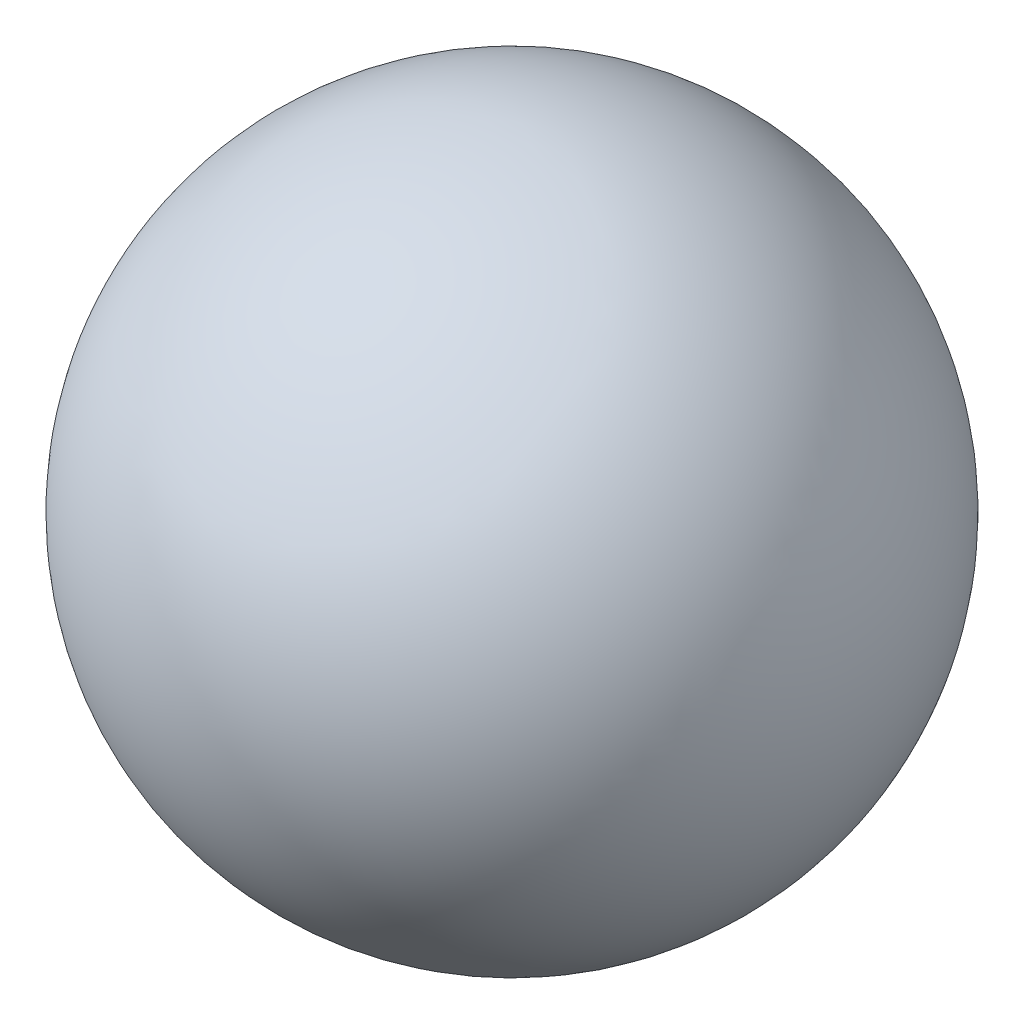
SolidWorks part; units mm, degrees
material "AISI 1020"
ref_plane "Plano superior" through (0, 0, 0) normal (0, 0, 1) x (1, 0, 0)
ref_plane "Plano frontal" through (0, 0, 0) normal (0, 1, 0) x (1, 0, 0)
ref_plane "Plano direito" through (0, 0, 0) normal (1, 0, 0) x (0, 0, -1)
sketch "Esboço1" plane through (0, 0, 0) normal (0, 1, 0) x (1, 0, 0)
  line L0 (5.9286, 0) -> (39.3263, 0) construction
  line L1 (46.6274, 0) -> (0, 0)
  line L3 (0, 8) -> (0, 0)
  arc A0 (46.6274, 0) -> (0, 8) centre (22.6274, 0) ccw
  point P5 (5.9286, -8)
  point P6 (77.652, -8)
  point P7 (5.9286, 8)
  point P8 (77.652, 8)
  dimension "D2" = 24
revolve "Revolução1" add sketch "Esboço1" angle 360 about L0
hole_wizard "Furo roscado de M161" positions "Esboço2" profile "Esboço3" tap size "M16" standard "DIN"
sketch "Esboço2" plane through (0, 0, 0) normal (-1, 0, 0) x (0, 0, 1)
  point P0 (0, 0)
sketch "Esboço3" plane through (0, 0, 0) normal (0, 1, 0) x (0, 0, 1)
  line L0 (0, 0) -> (0, 42.206)
  line L1 (0, 42.206) -> (7, 38)
  line L2 (7, 38) -> (7, 1.025)
  line L3 (7, 1.025) -> (8.025, 0)
  line L5 (8.025, 0) -> (0, 0)
  line L6 (-7, 1.025) -> (-8.025, 0) construction
  line L10 (0, 42.206) -> (-7, 38) construction
  line L11 (0, -6.35) -> (0, 107.95) construction
  dimension "Tap Drill Dia." = 14
  dimension "Tap Drill Depth" = 38
  dimension "Near C'Sink Dia." = 16.05
  dimension "Near C'Sink Angle" = 90
  dimension "Drill Angle" = 118
cosmetic thread "Rosca de furo1" parameters "D1"=30, "D2"=16
